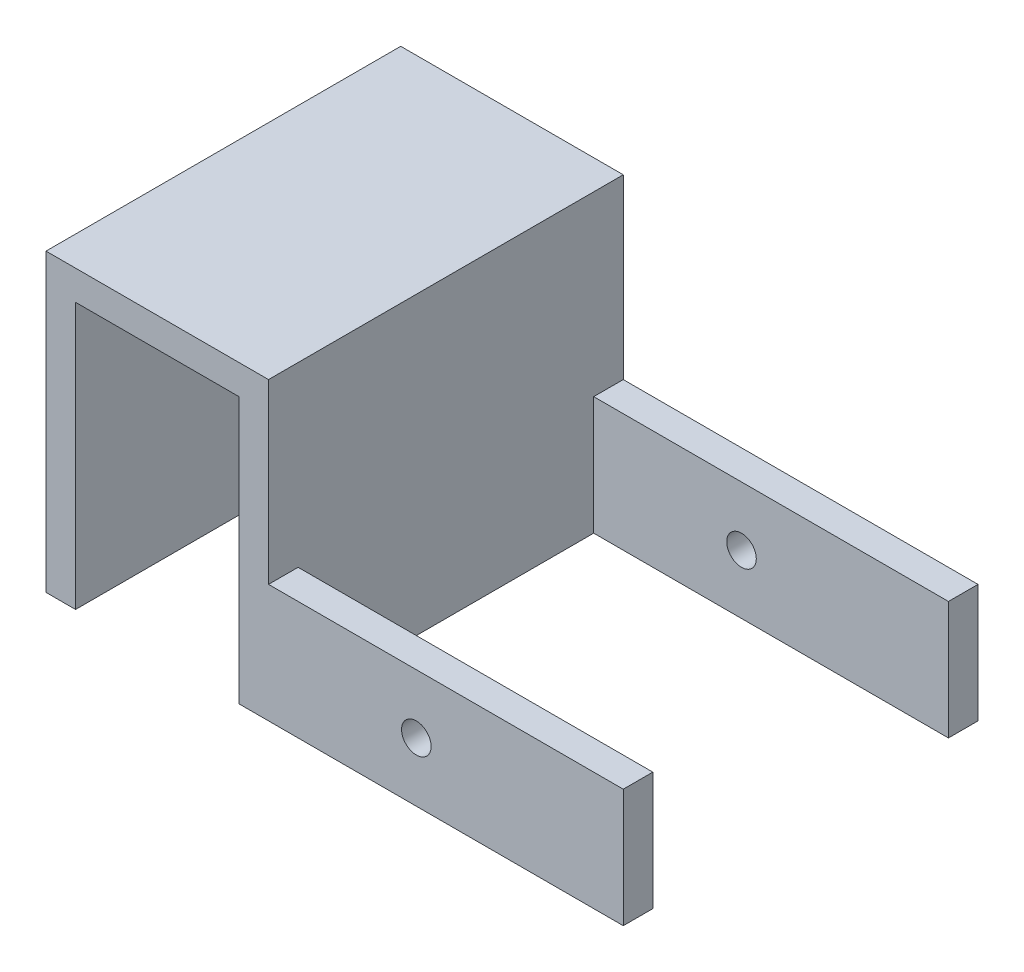
SolidWorks part; units mm, degrees
ref_plane "Front Plane" through (0, 0, 0) normal (0, 0, 1) x (1, 0, 0)
ref_plane "Top Plane" through (0, 0, 0) normal (0, 1, 0) x (1, 0, 0)
ref_plane "Right Plane" through (0, 0, 0) normal (1, 0, 0) x (0, 0, -1)
sketch "Sketch1" plane through (0, 0, 0) normal (0, 0, 1) x (1, 0, 0)
  line L0 (0, 0) -> (0, 50)
  line L1 (0, 50) -> (37.64, 50)
  line L2 (37.64, 50) -> (37.64, 0)
  line L3 (37.64, 0) -> (32.64, 0)
  line L4 (5, 0) -> (5, 45)
  line L5 (5, 45) -> (32.64, 45)
  line L6 (32.64, 45) -> (32.64, 0)
  line L7 (5, 0) -> (0, 0)
  dimension "D1" = 37.64
  dimension "D2" = 50
  dimension "D3" = 5
  dimension "D4" = 5
  dimension "D5" = 5
extrude "Boss-Extrude1" add sketch "Sketch1" along normal mid plane 60
sketch "Sketch3" plane through (0, 0, 0) normal (0, -1, 0) x (1, 0, 0)
  line L0 (37.64, 30) -> (97.64, 30)
  line L4 (97.64, 30) -> (97.64, 25)
  line L5 (97.64, 25) -> (37.64, 25)
  line L6 (37.64, 30) -> (37.64, -30) construction
  line L7 (37.64, 25) -> (37.64, 30)
  line L8 (0, 0) -> (108.101, 0) construction
  line L9 (37.64, -25) -> (37.64, -30)
  line L10 (97.64, -25) -> (37.64, -25)
  line L11 (97.64, -30) -> (97.64, -25)
  line L12 (37.64, -30) -> (97.64, -30)
  dimension "D1" = 5
  dimension "D2" = 60
extrude "Boss-Extrude2" add sketch "Sketch3" against normal blind 20
sketch "Sketch4" plane through (0, 0, 30) normal (0, 0, 1) x (1, 0, 0)
  line L0 (97.64, 20) -> (37.64, 20) construction
  line L1 (97.64, 20) -> (97.64, 0) construction
  circle A0 centre (62.64, 10) radius 2.5
  point P4 (64.2613, 10)
  point P5 (0, 0)
  dimension "D1" = 5
  dimension "D2" = 10
  dimension "D3" = 35
extrude "Cut-Extrude1" cut sketch "Sketch4" against normal through all
